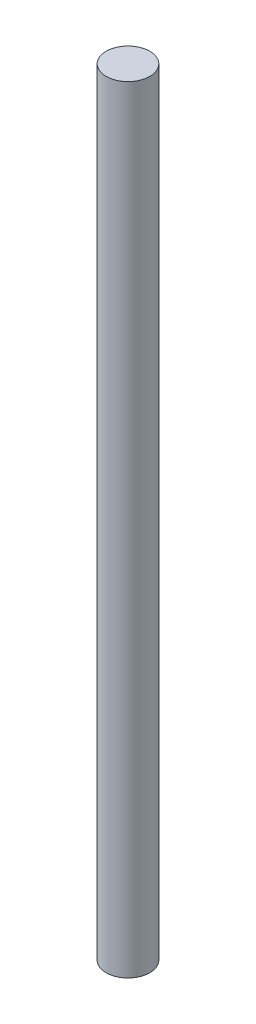
SolidWorks part; units mm, degrees
ref_plane "Front Plane" through (0, 0, 0) normal (0, 0, 1) x (1, 0, 0)
ref_plane "Top Plane" through (0, 0, 0) normal (0, 1, 0) x (1, 0, 0)
ref_plane "Right Plane" through (0, 0, 0) normal (1, 0, 0) x (0, 0, -1)
sketch "Sketch1" plane through (0, 0, 0) normal (0, 1, 0) x (1, 0, 0)
  circle A0 centre (0, 0) radius 5.62
  dimension "D1" = 11.24
extrude "Boss-Extrude1" add sketch "Sketch1" along normal blind 200
